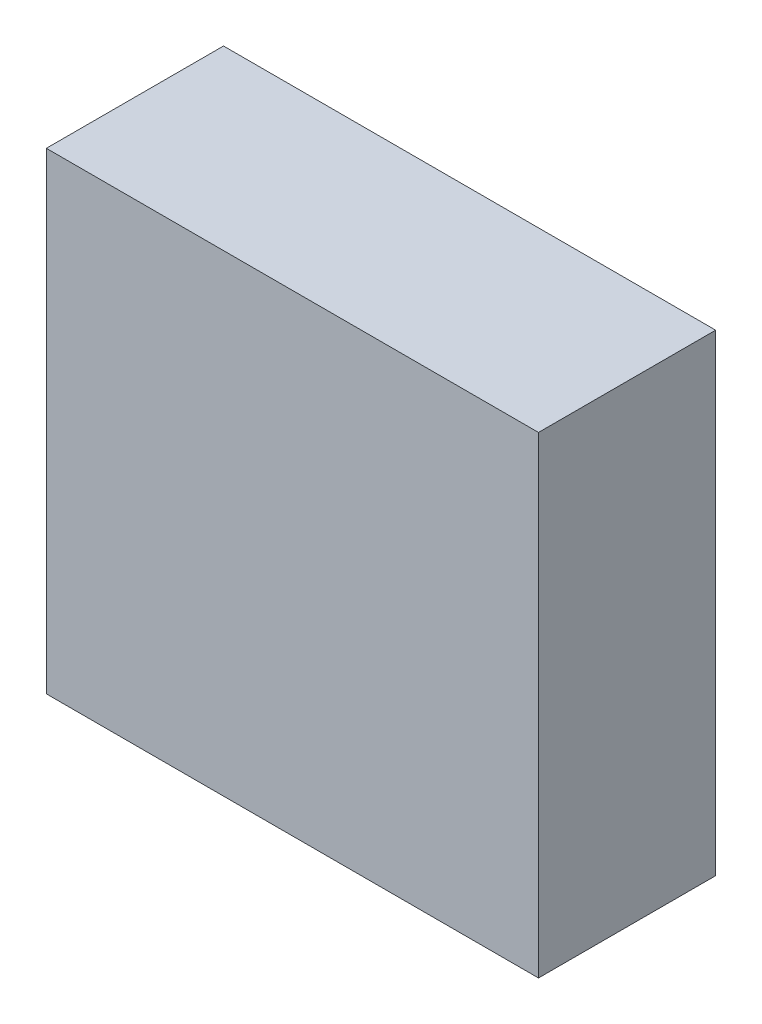
SolidWorks part; units mm, degrees
ref_plane "Front Plane" through (0, 0, 0) normal (0, 0, 1) x (1, 0, 0)
ref_plane "Top Plane" through (0, 0, 0) normal (0, 1, 0) x (1, 0, 0)
ref_plane "Right Plane" through (0, 0, 0) normal (1, 0, 0) x (0, 0, -1)
sketch "Sketch1" plane through (0, 0, 0) normal (0, 0, 1) x (1, 0, 0)
  line L1 (12.5, -12) -> (-12.5, -12)
  line L2 (12.5, -12) -> (12.5, 12)
  line L3 (12.5, 12) -> (-12.5, 12)
  line L4 (-12.5, -12) -> (-12.5, 12)
  line L5 (12.5, -12) -> (-12.5, 12) construction
  line L6 (12.5, 12) -> (-12.5, -12) construction
  point P0 (0, 0)
  dimension "D1" = 25
  dimension "D2" = 24
extrude "Boss-Extrude1" add sketch "Sketch1" along normal blind 9
